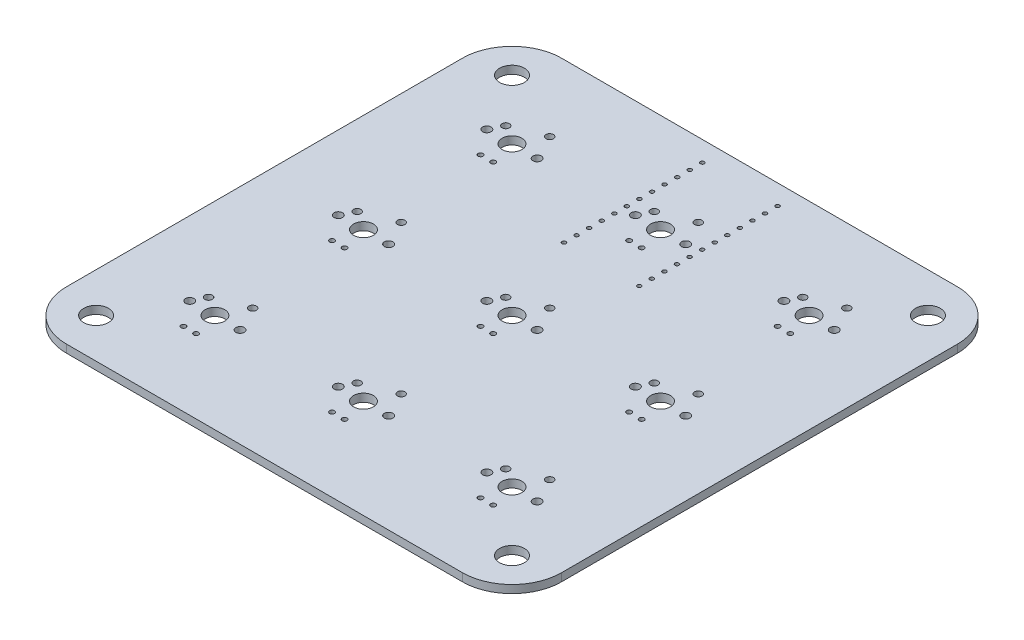
SolidWorks part; units mm, degrees
ref_plane "Front Plane" through (0, 0, 0) normal (0, 0, 1) x (1, 0, 0)
ref_plane "Top Plane" through (0, 0, 0) normal (0, 1, 0) x (1, 0, 0)
ref_plane "Right Plane" through (0, 0, 0) normal (1, 0, 0) x (0, 0, -1)
sketch "Sketch1" plane through (0, 0, 0) normal (0, 1, 0) x (1, 0, 0)
  line L1 (40, -50) -> (-40, -50)
  line L2 (50, -40) -> (50, 40)
  line L3 (40, 50) -> (-40, 50)
  line L4 (-50, -40) -> (-50, 40)
  line L5 (50, -50) -> (-50, 50) construction
  line L6 (50, 50) -> (-50, -50) construction
  arc A0 (-50, -40) -> (-40, -50) centre (-40, -40) ccw
  arc A1 (40, -50) -> (50, -40) centre (40, -40) ccw
  arc A2 (50, 40) -> (40, 50) centre (40, 40) ccw
  arc A3 (-40, 50) -> (-50, 40) centre (-40, 40) ccw
  point P0 (0, 0)
  dimension "D2" = 10
  dimension "D1" = 100
extrude "Boss-Extrude1" add sketch "Sketch1" along normal blind 1.6
sketch "Sketch2" plane through (0, 1.6, 0) normal (0, 1, 0) x (1, 0, 0)
  circle A0 centre (-42, 42) radius 2.5
  circle A1 centre (42, 42) radius 2.5
  circle A2 centre (42, -42) radius 2.5
  circle A3 centre (-42, -42) radius 2.5
  dimension "D1" = 5
  dimension "D2" = 42
  dimension "D3" = 42
  dimension "D6" = 84
  dimension "D7" = 84
  dimension "D4" = 2
  dimension "D5" = 2
extrude "Cut-Extrude1" cut sketch "Sketch2" against normal blind 1.6
sketch "Sketch3" plane through (0, 1.6, 0) normal (0, 1, 0) x (1, 0, 0)
  circle A0 centre (-7.5, 18) radius 0.4
  circle A1 centre (7.7, 18) radius 0.4
  circle A2 centre (7.7, 20.54) radius 0.4
  circle A3 centre (7.7, 23.08) radius 0.4
  circle A4 centre (7.7, 25.62) radius 0.4
  circle A5 centre (7.7, 28.16) radius 0.4
  circle A6 centre (7.7, 30.7) radius 0.4
  circle A7 centre (7.7, 33.24) radius 0.4
  circle A8 centre (7.7, 35.78) radius 0.4
  circle A9 centre (7.7, 38.32) radius 0.4
  circle A10 centre (7.7, 40.86) radius 0.4
  circle A11 centre (7.7, 43.4) radius 0.4
  circle A12 centre (7.7, 45.94) radius 0.4
  circle A13 centre (-7.5, 20.54) radius 0.4
  circle A14 centre (-7.5, 23.08) radius 0.4
  circle A15 centre (-7.5, 25.62) radius 0.4
  circle A16 centre (-7.5, 28.16) radius 0.4
  circle A17 centre (-7.5, 30.7) radius 0.4
  circle A18 centre (-7.5, 33.24) radius 0.4
  circle A19 centre (-7.5, 35.78) radius 0.4
  circle A20 centre (-7.5, 38.32) radius 0.4
  circle A21 centre (-7.5, 40.86) radius 0.4
  circle A22 centre (-7.5, 43.4) radius 0.4
  circle A23 centre (-7.5, 45.94) radius 0.4
  dimension "D1" = 0.8
  dimension "D4" = 2
  dimension "D2" = 7.5
  dimension "D3" = 18
  dimension "D6" = 15.2
  dimension "D5" = 12
extrude "Cut-Extrude2" cut sketch "Sketch3" against normal blind 1.6
sketch "Sketch4" plane through (0, 1.6, 0) normal (0, 1, 0) x (1, 0, 0)
  circle A0 centre (-30, 30) radius 1.9939
  circle A1 centre (0, 30) radius 1.9939
  circle A2 centre (30, 30) radius 1.9939
  circle A3 centre (0, 0) radius 1.9939
  circle A4 centre (30, 0) radius 1.9939
  circle A5 centre (0, -30) radius 1.9939
  circle A6 centre (30, -30) radius 1.9939
  circle A7 centre (-30, 0) radius 1.9939
  circle A8 centre (-30, -30) radius 1.9939
  dimension "D1" = 3.9878
  dimension "D2" = 30
  dimension "D3" = 30
  dimension "D4" = 3
  dimension "D5" = 3
extrude "Cut-Extrude3" cut sketch "Sketch4" against normal blind 1.6
sketch "Sketch5" plane through (0, 1.6, 0) normal (0, 1, 0) x (1, 0, 0)
  line L0 (-30, 31.9939) -> (-30, 28.0061) construction
  line L1 (0, 31.9939) -> (0, 28.0061) construction
  line L2 (30, 31.9939) -> (30, 28.0061) construction
  line L3 (0, 1.9939) -> (0, -1.9939) construction
  line L4 (30, 1.9939) -> (30, -1.9939) construction
  line L5 (0, -28.0061) -> (0, -31.9939) construction
  line L6 (30, -28.0061) -> (30, -31.9939) construction
  line L7 (-30, 1.9939) -> (-30, -1.9939) construction
  line L8 (-30, -28.0061) -> (-30, -31.9939) construction
  circle A0 centre (-33.81, 32.54) radius 0.7493
  circle A1 centre (-27.46, 35.08) radius 0.7493
  circle A2 centre (-35.08, 30) radius 0.8509
  circle A3 centre (-24.92, 30) radius 0.8509
  circle A4 centre (-31.27, 24.92) radius 0.4953
  circle A5 centre (-28.73, 24.92) radius 0.4953
  circle A6 centre (-30, 30) radius 1.9939 construction
  circle A39 centre (-3.81, 32.54) radius 0.7493
  circle A40 centre (2.54, 35.08) radius 0.7493
  circle A41 centre (-5.08, 30) radius 0.8509
  circle A42 centre (5.08, 30) radius 0.8509
  circle A43 centre (-1.27, 24.92) radius 0.4953
  circle A44 centre (1.27, 24.92) radius 0.4953
  circle A45 centre (26.19, 32.54) radius 0.7493
  circle A46 centre (32.54, 35.08) radius 0.7493
  circle A47 centre (24.92, 30) radius 0.8509
  circle A48 centre (35.08, 30) radius 0.8509
  circle A49 centre (28.73, 24.92) radius 0.4953
  circle A50 centre (31.27, 24.92) radius 0.4953
  circle A51 centre (-3.81, 2.54) radius 0.7493
  circle A52 centre (2.54, 5.08) radius 0.7493
  circle A53 centre (-5.08, 0) radius 0.8509
  circle A54 centre (5.08, 0) radius 0.8509
  circle A55 centre (-1.27, -5.08) radius 0.4953
  circle A56 centre (1.27, -5.08) radius 0.4953
  circle A57 centre (26.19, 2.54) radius 0.7493
  circle A58 centre (32.54, 5.08) radius 0.7493
  circle A59 centre (24.92, 0) radius 0.8509
  circle A60 centre (35.08, 0) radius 0.8509
  circle A61 centre (28.73, -5.08) radius 0.4953
  circle A62 centre (31.27, -5.08) radius 0.4953
  circle A63 centre (-3.81, -27.46) radius 0.7493
  circle A64 centre (2.54, -24.92) radius 0.7493
  circle A65 centre (-5.08, -30) radius 0.8509
  circle A66 centre (5.08, -30) radius 0.8509
  circle A67 centre (-1.27, -35.08) radius 0.4953
  circle A68 centre (1.27, -35.08) radius 0.4953
  circle A69 centre (26.19, -27.46) radius 0.7493
  circle A70 centre (32.54, -24.92) radius 0.7493
  circle A71 centre (24.92, -30) radius 0.8509
  circle A72 centre (35.08, -30) radius 0.8509
  circle A73 centre (28.73, -35.08) radius 0.4953
  circle A74 centre (31.27, -35.08) radius 0.4953
  circle A75 centre (-33.81, 2.54) radius 0.7493
  circle A76 centre (-27.46, 5.08) radius 0.7493
  circle A77 centre (-35.08, 0) radius 0.8509
  circle A78 centre (-24.92, 0) radius 0.8509
  circle A79 centre (-31.27, -5.08) radius 0.4953
  circle A80 centre (-28.73, -5.08) radius 0.4953
  circle A81 centre (-33.81, -27.46) radius 0.7493
  circle A82 centre (-27.46, -24.92) radius 0.7493
  circle A83 centre (-35.08, -30) radius 0.8509
  circle A84 centre (-24.92, -30) radius 0.8509
  circle A85 centre (-31.27, -35.08) radius 0.4953
  circle A86 centre (-28.73, -35.08) radius 0.4953
  point P18 (-30, 30)
  dimension "D11" = 1.7018
  dimension "D12" = 1.7018
  dimension "D13" = 1.4986
  dimension "D14" = 1.4986
  dimension "D15" = 0.9906
  dimension "D16" = 0.9906
  dimension "D1" = 5.08
  dimension "D2" = 5.08
  dimension "D3" = 2.54
  dimension "D4" = 3.81
  dimension "D5" = 2.54
  dimension "D6" = 5.08
  dimension "D7" = 5.08
  dimension "D8" = 5.08
  dimension "D9" = 1.27
  dimension "D10" = 1.27
  dimension "D17" = 3
  dimension "D18" = 3
extrude "Cut-Extrude4" cut sketch "Sketch5" against normal blind 1.6
